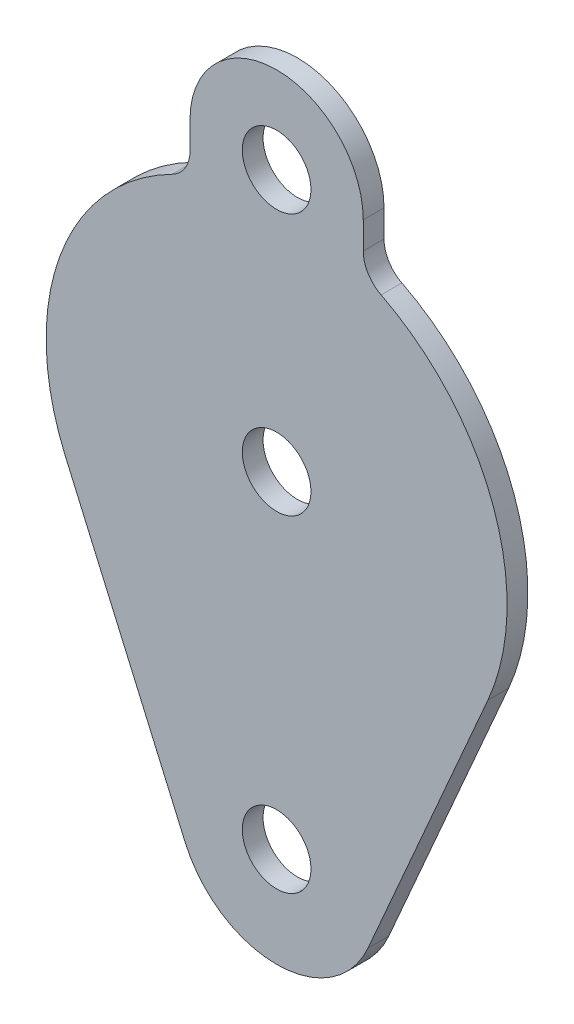
SolidWorks part; units mm, degrees
material "AISI 1020"
ref_plane "Plano frontal" through (0, 0, 0) normal (0, 0, 1) x (1, 0, 0)
ref_plane "Plano superior" through (0, 0, 0) normal (0, 1, 0) x (1, 0, 0)
ref_plane "Plano direito" through (0, 0, 0) normal (1, 0, 0) x (0, 0, -1)
sketch "Esboço1" plane through (0, 0, 0) normal (0, 0, 1) x (1, 0, 0)
  line L0 (13.9769, -56.1) -> (32.3072, -14.1)
  line L1 (0, -9.4879) -> (0, -16.9859) construction
  line L2 (-13.9769, -56.1) -> (-32.3072, -14.1)
  line L3 (13.25, 40) -> (13.25, 32.665)
  line L4 (-13.25, 40) -> (-13.25, 32.665)
  circle A0 centre (0, 40) radius 5.25
  circle A1 centre (0, 0) radius 5.25
  circle A2 centre (0, -50) radius 5.25
  circle A3 centre (0, 40) radius 13.25
  circle A4 centre (0, 0) radius 35.25
  circle A5 centre (0, -50) radius 15.25
  dimension "D1" = 10.5
  dimension "D2" = 10.5
  dimension "D3" = 10.5
  dimension "D4" = 40
  dimension "D5" = 50
  dimension "D6" = 8
  dimension "D7" = 30
  dimension "D8" = 10
extrude "Extrusão1" add sketch "Esboço1" along normal blind 3.175 contours A3 A4 A0 | A4 A3 A0 | A4 A5 A3 A1 | A5 A4 A2 | A5 A4 A2 | A4 A5 L0 | L2 A5 A4 | A4 L3 A3 | A4 A3 L4
fillet "Filete1" radius 5 2 edges at (13.25, 32.665, 1.5875) (-13.25, 32.665, 1.5875)
